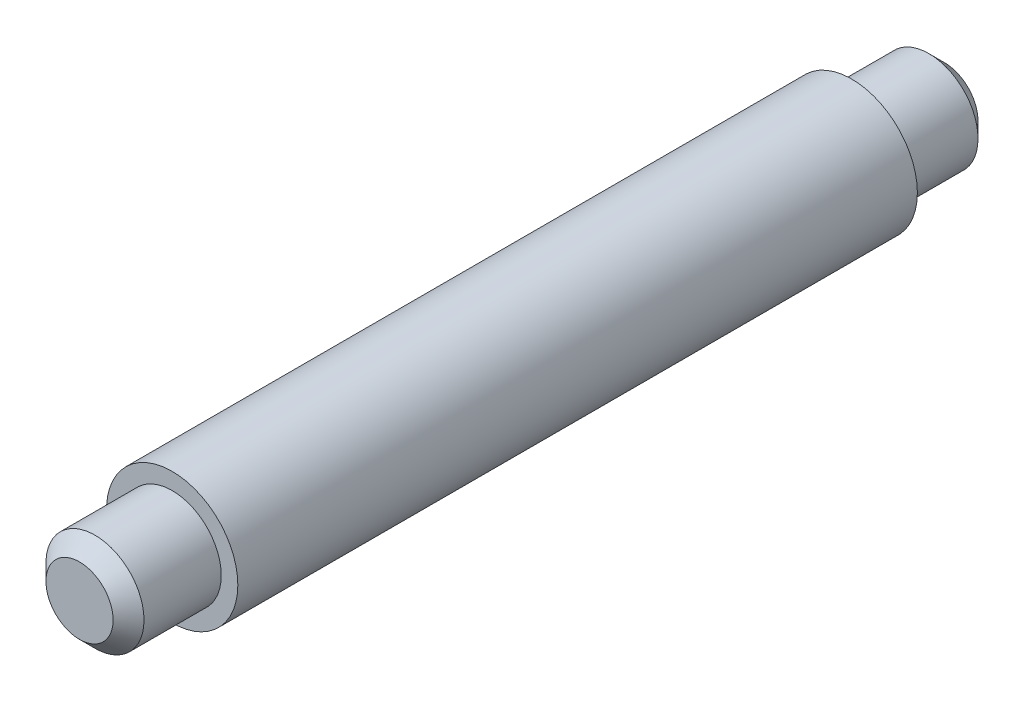
SolidWorks part; units mm, degrees
ref_plane "Front Plane" through (0, 0, 0) normal (0, 0, 1) x (1, 0, 0)
ref_plane "Top Plane" through (0, 0, 0) normal (0, 1, 0) x (1, 0, 0)
ref_plane "Right Plane" through (0, 0, 0) normal (1, 0, 0) x (0, 0, -1)
sketch "Sketch1" plane through (0, 0, 0) normal (0, 0, 1) x (1, 0, 0)
  circle A0 centre (0, 0) radius 4.25
  dimension "D1" = 8.5
extrude "Boss-Extrude1" add sketch "Sketch1" along normal mid plane 44
sketch "Sketch2" plane through (0, 0, 22) normal (0, 0, 1) x (1, 0, 0)
  circle A0 centre (0, 0) radius 3.175
  dimension "D1" = 6.35
extrude "Boss-Extrude2" add sketch "Sketch2" along normal blind 6
chamfer "Chamfer1" distance 1 angle 45 1 edges at (3.175, 0, 28)
mirror "Mirror1" about plane through (0, 0, 0) normal (0, 0, 1) of "Boss-Extrude2"
chamfer "Chamfer2" distance 1 angle 45 1 edges at (3.175, 0, -28)
